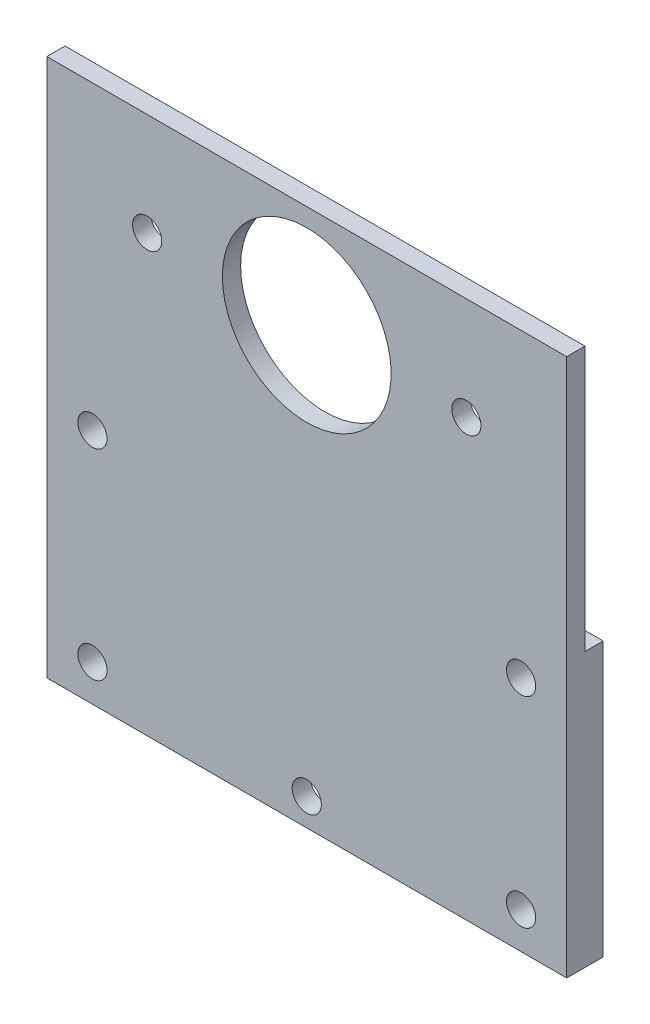
SolidWorks part; units mm, degrees
ref_plane "Ebene vorne" through (0, 0, 0) normal (0, 0, 1) x (1, 0, 0)
ref_plane "Ebene oben" through (0, 0, 0) normal (0, 1, 0) x (1, 0, 0)
ref_plane "Ebene rechts" through (0, 0, 0) normal (1, 0, 0) x (0, 0, -1)
sketch "Skizze1" plane through (0, 0, 0) normal (0, 0, 1) x (1, 0, 0)
  line L0 (0, 0) -> (0, 72.9146) construction
  line L1 (-28.5, 59) -> (28.5, 59)
  line L2 (28.5, 59) -> (28.5, 0)
  line L3 (28.5, 0) -> (-28.5, 0)
  line L4 (-28.5, 59) -> (-28.5, 0)
  point P7 (0, 59)
  dimension "D1" = 57
  dimension "D2" = 59
extrude "Grundkörper" add sketch "Skizze1" along normal blind 2
sketch "Skizze2" plane through (0, 0, 0) normal (0, 0, -1) x (-1, 0, 0)
  line L0 (0, 0) -> (0, 59.4137) construction
  line L1 (-18.082, 47.75) -> (18.082, 47.75) construction
  line L2 (-28.5, 59) -> (28.5, 59) construction
  circle A0 centre (0, 47.75) radius 9.25
  circle A1 centre (-17.5, 47.75) radius 1.6
  circle A2 centre (17.5, 47.75) radius 1.6
  dimension "D1" = 3.2
  dimension "D2" = 18.5
  dimension "D3" = 11.25
  dimension "D4" = 35
extrude "Bohrungen_Kugelroller" cut sketch "Skizze2" against normal through all
sketch "Skizze3" plane through (0, 0, 0) normal (0, 0, -1) x (-1, 0, 0)
  line L0 (0, 59) -> (0, -0.4438) construction
  line L1 (-28.5, 59) -> (28.5, 59) construction
  line L2 (-28.5, 30) -> (-18.5, 30)
  line L3 (-28.5, 0) -> (-28.5, 59) construction
  line L4 (-18.5, 30) -> (-18.5, 0)
  line L5 (28.5, 0) -> (18.5, 0)
  line L6 (28.5, 30) -> (28.5, 0)
  line L7 (-28.5, 30) -> (-28.5, 0)
  line L8 (-28.5, 0) -> (-18.5, 0)
  line L9 (28.5, 0) -> (-28.5, 0) construction
  line L10 (18.5, 30) -> (18.5, 0)
  line L11 (28.5, 30) -> (18.5, 30)
  dimension "D1" = 10
  dimension "D2" = 30
extrude "Aufsatz_Getriebehalter" add sketch "Skizze3" along normal blind 2
sketch "Skizze4" plane through (0, 0, -2) normal (0, 0, -1) x (-1, 0, 0)
  line L0 (0, 57.8388) -> (0, -14.2703) construction
  line L1 (24, 15) -> (-24, 15) construction
  line L2 (-23.5, 30) -> (-23.5, -0.0042) construction
  line L3 (24, 22.0317) -> (24, 7.9683) construction
  line L4 (-18.5, 15) -> (-29.1223, 15) construction
  line L5 (-18.5, 0) -> (-18.5, 30) construction
  line L7 (-18.5, 30) -> (-28.5, 30) construction
  circle A0 centre (-23.5, 26) radius 1.6
  circle A1 centre (23.5, 26) radius 1.6
  circle A2 centre (23.5, 4) radius 1.6
  circle A3 centre (-23.5, 4) radius 1.6
  point P10 (0, 15)
  point P24 (0, 0)
  dimension "D1" = 3.2
  dimension "D2" = 22
extrude "Bohrungen_Getriebehalter" cut sketch "Skizze4" against normal through all
sketch "Skizze5" plane through (0, 0, 0) normal (0, 0, -1) x (-1, 0, 0)
  line L0 (0, 61.2734) -> (0, -5.0948) construction
  line L1 (18.5, 0) -> (-18.5, 0) construction
  circle A0 centre (0, 3) radius 1.6
  dimension "D1" = 3.2
  dimension "D2" = 3
extrude "Bohrung_Halterung" cut sketch "Skizze5" against normal through all
